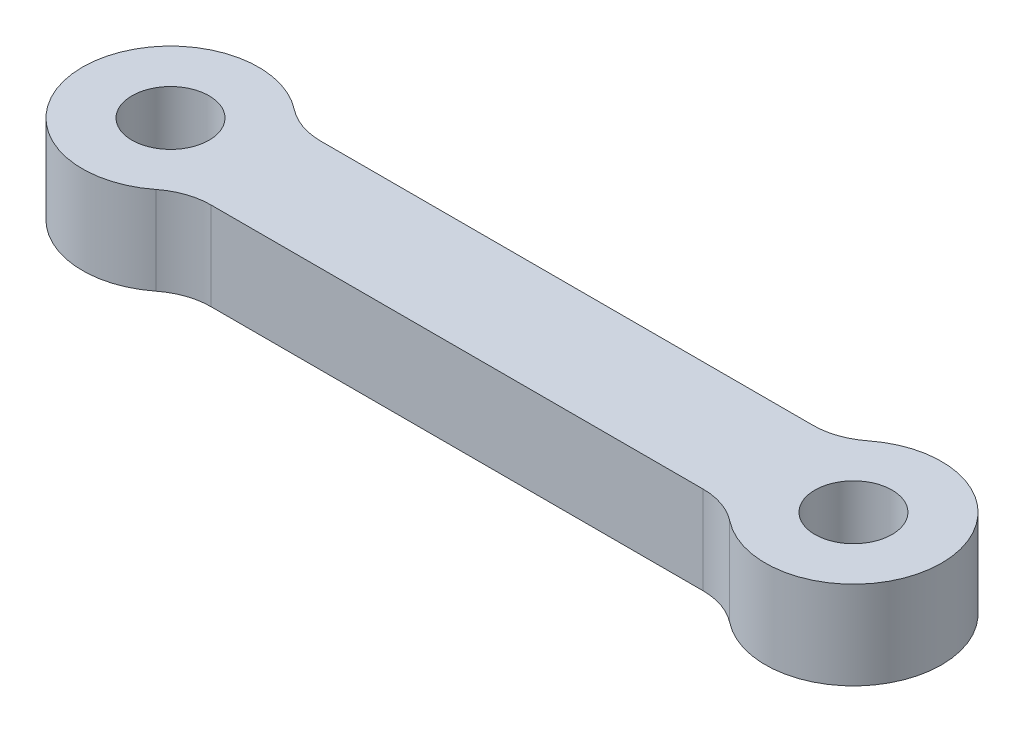
SolidWorks part; units mm, degrees
ref_plane "前视基准面" through (0, 0, 0) normal (0, 0, 1) x (1, 0, 0)
ref_plane "上视基准面" through (0, 0, 0) normal (0, 1, 0) x (1, 0, 0)
ref_plane "右视基准面" through (0, 0, 0) normal (1, 0, 0) x (0, 0, -1)
sketch "草图1" plane through (0, 0, 0) normal (0, 1, 0) x (1, 0, 0)
  line L0 (-27.8775, 2.5) -> (-3.1225, 2.5)
  line L1 (-31, 0) -> (0, 0) construction
  line L2 (-3.1225, -2.5) -> (-27.8775, -2.5)
  arc A0 (-27.8775, 2.5) -> (-27.8775, -2.5) centre (-31, 0) ccw
  arc A1 (-3.1225, -2.5) -> (-3.1225, 2.5) centre (0, 0) ccw
  circle A2 centre (-31, 0) radius 1.75
  circle A3 centre (0, 0) radius 1.75
  dimension "D2" = 3.5
  dimension "D3" = 8
  dimension "D4" = 8
  dimension "D5" = 3.5
  dimension "D1" = 5
  dimension "D6" = 31
extrude "凸台-拉伸1" add sketch "草图1" along normal blind 4
fillet "圆角1" radius 3 4 edges at (-3.1225, 2, -2.5) (-27.8775, 2, -2.5) (-27.8775, 2, 2.5) (-3.1225, 2, 2.5)
